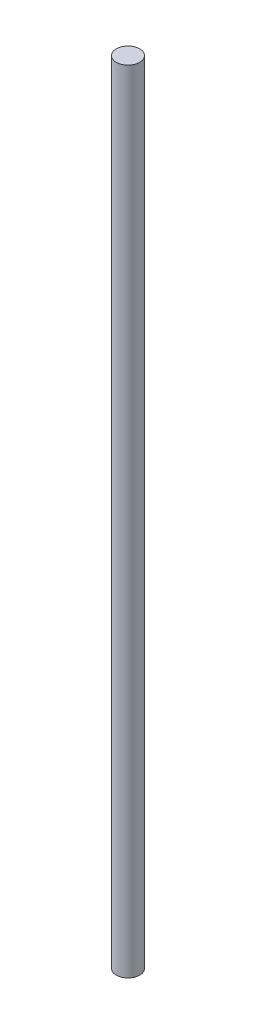
SolidWorks part; units mm, degrees
other "标注1"
sketch "草图3" plane through (-22.25, 4, -10) normal (-0.231, 0.6469, -0.7268) x (-0.9696, -0.2151, 0.1167)
ref_plane "前视基准面" through (0, 0, 0) normal (0, 0, 1) x (1, 0, 0)
ref_plane "上视基准面" through (0, 0, 0) normal (0, 1, 0) x (1, 0, 0)
ref_plane "右视基准面" through (0, 0, 0) normal (1, 0, 0) x (0, 0, -1)
other "Configuration Table"
sketch "草图4" plane through (0, 0, 0) normal (0, 1, 0) x (1, 0, 0)
  circle A1 centre (0, 0) radius 0.5
  dimension "D2" = 1
extrude "凸台-拉伸1" add sketch "草图4" along normal blind 33.8
